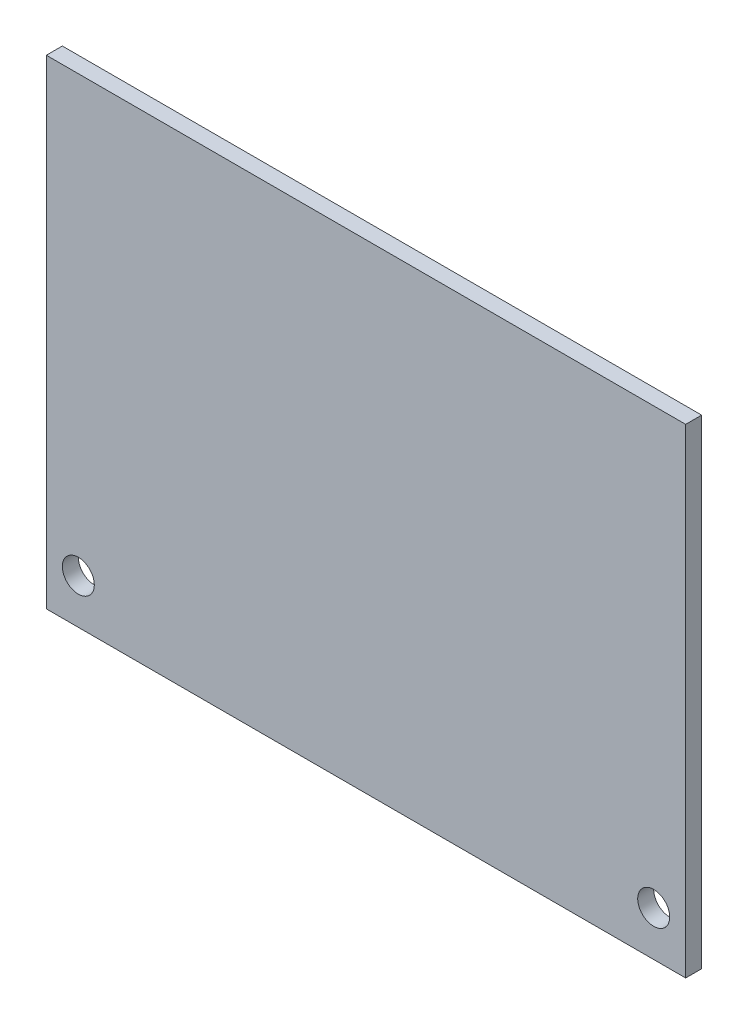
SolidWorks part; units mm, degrees
ref_plane "Přední rovina" through (0, 0, 0) normal (0, 0, 1) x (1, 0, 0)
ref_plane "Horní rovina" through (0, 0, 0) normal (0, 1, 0) x (1, 0, 0)
ref_plane "Pravá rovina" through (0, 0, 0) normal (1, 0, 0) x (0, 0, -1)
sketch "Skica1" plane through (0, 0, 0) normal (0, 0, 1) x (1, 0, 0)
  line L1 (-20, -15) -> (20, -15)
  line L2 (-20, -15) -> (-20, 15)
  line L3 (-20, 15) -> (20, 15)
  line L4 (20, -15) -> (20, 15)
  line L5 (-20, -15) -> (20, 15) construction
  line L6 (-20, 15) -> (20, -15) construction
  point P0 (0, 0)
  dimension "D1" = 40
  dimension "D2" = 30
extrude "Přidat vysunutím1" add sketch "Skica1" along normal blind 1
sketch "Skica2" plane through (0, 0, 1) normal (0, 0, 1) x (1, 0, 0)
  line L0 (-20, -15) -> (20, -15) construction
  line L1 (-20, 15) -> (-20, -15) construction
  line L2 (20, -15) -> (20, 15) construction
  circle A0 centre (18, -12.2) radius 1
  circle A1 centre (-18, -12.2) radius 1
  dimension "D1" = 2
  dimension "D4" = 2
  dimension "D2" = 2.8
  dimension "D3" = 2.8
  dimension "D5" = 2
  dimension "D6" = 2
extrude "Odebrat vysunutím1" cut sketch "Skica2" against normal blind 1
